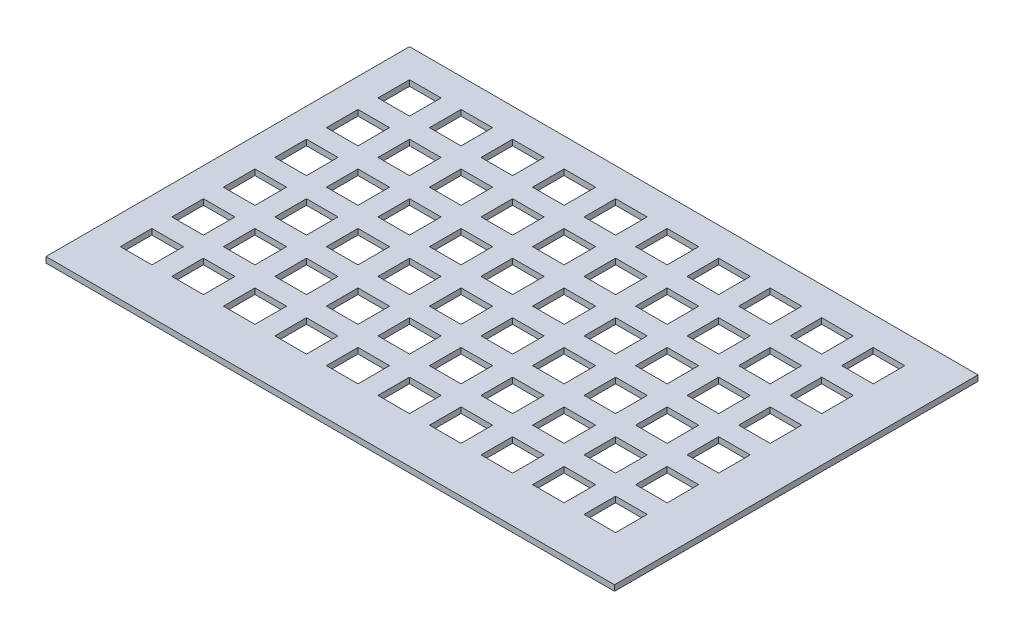
SolidWorks part; units mm, degrees
ref_plane "Front Plane" through (0, 0, 0) normal (0, 0, 1) x (1, 0, 0)
ref_plane "Top Plane" through (0, 0, 0) normal (0, 1, 0) x (1, 0, 0)
ref_plane "Right Plane" through (0, 0, 0) normal (1, 0, 0) x (0, 0, -1)
sketch "Sketch1" plane through (0, 0, 0) normal (0, 1, 0) x (1, 0, 0)
  line L1 (126.1115, -80.6391) -> (-126.1115, -80.6391)
  line L2 (126.1115, -80.6391) -> (126.1115, 80.6391)
  line L3 (126.1115, 80.6391) -> (-126.1115, 80.6391)
  line L4 (-126.1115, -80.6391) -> (-126.1115, 80.6391)
  line L5 (126.1115, -80.6391) -> (-126.1115, 80.6391) construction
  line L6 (126.1115, 80.6391) -> (-126.1115, -80.6391) construction
  point P1 (0, 0)
  point P6 (0, 0)
  point P7 (126.1115, -80.6391)
extrude "Boss-Extrude1" add sketch "Sketch1" against normal blind 2.54
sketch "Sketch2" plane through (0, 0, 0) normal (0, 1, 0) x (1, 0, 0)
  line L0 (126.1115, 80.6391) -> (-126.1115, 80.6391) construction
  line L1 (-99.4115, 53.9391) -> (-113.4115, 53.9391)
  line L2 (-99.4115, 53.9391) -> (-99.4115, 67.9391)
  line L3 (-99.4115, 67.9391) -> (-113.4115, 67.9391)
  line L4 (-113.4115, 53.9391) -> (-113.4115, 67.9391)
  line L5 (-99.4115, 53.9391) -> (-113.4115, 67.9391) construction
  line L6 (-99.4115, 67.9391) -> (-113.4115, 53.9391) construction
  line L7 (-126.1115, 80.6391) -> (-126.1115, -80.6391) construction
  point P0 (-106.4115, 60.9391)
  dimension "D1" = 14
  dimension "D2" = 14
  dimension "D3" = 12.7
  dimension "D4" = 12.7
extrude "Cut-Extrude1" cut sketch "Sketch2" against normal through all
pattern_linear "LPattern2" count 6 spacing 22.86 along (0, 0, 1) count 10 spacing 22.86 along (1, 0, 0) of "Cut-Extrude1"
